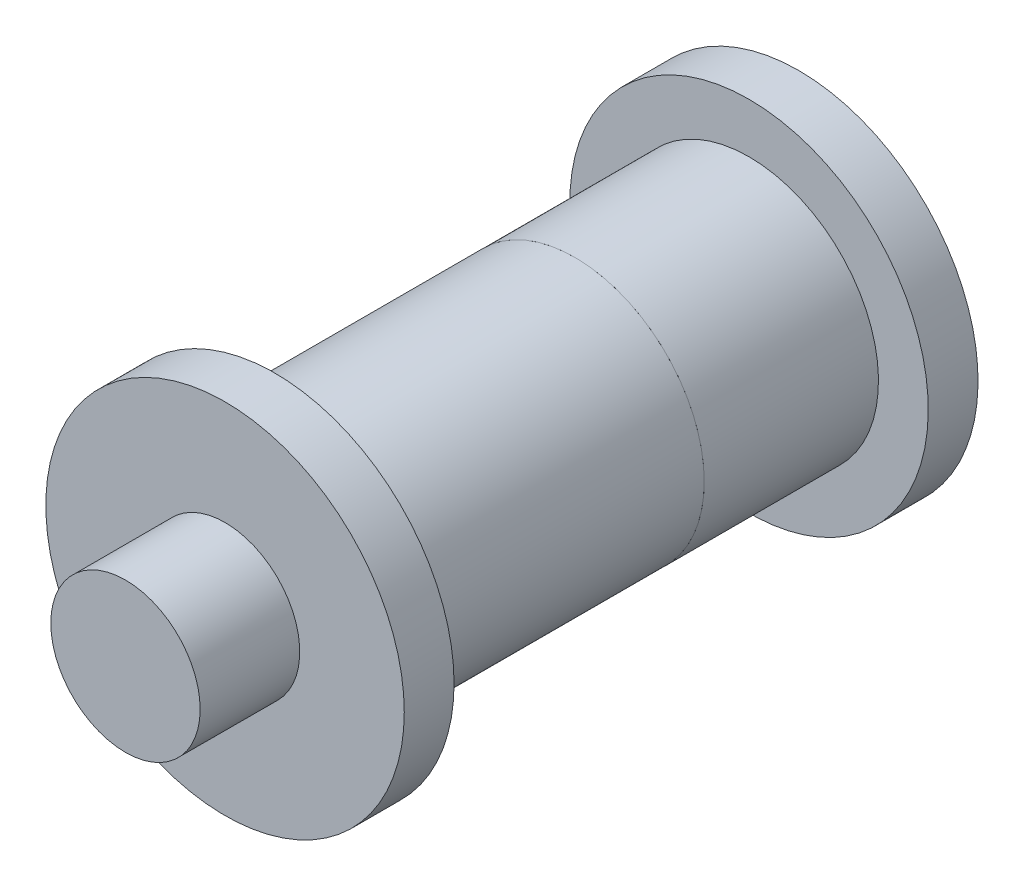
SolidWorks part; units mm, degrees
material "ABS"
ref_plane "Front Plane" through (0, 0, 0) normal (0, 0, 1) x (1, 0, 0)
ref_plane "Top Plane" through (0, 0, 0) normal (0, 1, 0) x (1, 0, 0)
ref_plane "Right Plane" through (0, 0, 0) normal (1, 0, 0) x (0, 0, -1)
sketch "Sketch2" plane through (0, 0, 0) normal (1, 0, 0) x (0, 0, -1)
  line L0 (0, 0) -> (0, 5.2)
  line L1 (0, 5.2) -> (7, 5.2)
  line L2 (7, 5.2) -> (7, 7.2)
  line L3 (7, 7.2) -> (9, 7.2)
  line L5 (11, 0) -> (0, 0)
  line L6 (9, 7.2) -> (9, 2.5)
  line L7 (9, 2.5) -> (11, 2.5)
  line L8 (11, 2.5) -> (11, 0)
  point P2 (5.9162, 5.2)
  point P7 (0, 0)
  point P11 (11.008, 0)
  point P12 (0, 0)
  point P13 (13.0983, 0)
  point P14 (15.3628, 0)
  dimension "D3" = 5.2
  dimension "D4" = 2
  dimension "D1" = 2
  dimension "D2" = 2.5
  dimension "D5" = 11
  dimension "D6" = 2
revolve "Revolve1" add sketch "Sketch2" angle 360 about L5
sketch "Sketch4" plane through (0, 0, -11) normal (0, 0, -1) x (-1, 0, 0)
  circle A0 centre (0, 0) radius 1.6
  dimension "D1" = 3.2
extrude "Cut-Extrude2" cut sketch "Sketch4" against normal blind 0.5
sketch "Sketch5" plane through (0, 0, 0) normal (1, 0, 0) x (0, 0, -1)
  line L0 (0, 0) -> (0, 5.2)
  line L1 (0, 5.2) -> (-12.05, 5.2)
  line L2 (-12.05, 5.2) -> (-12.05, 7.2)
  line L3 (-12.05, 7.2) -> (-14.05, 7.2)
  line L4 (-14.05, 7.2) -> (-14.05, 0)
  line L7 (-14.05, 0) -> (0, 0)
  line L8 (7, 7.2) -> (7, -7.2) construction
  line L9 (9, 7.2) -> (7, 7.2) construction
  point P9 (-14.05, 0)
  point P14 (-14.05, 0.0855)
  dimension "D1" = 19.05
  dimension "D2" = 2
revolve "Revolve2" add sketch "Sketch5" angle 360 about L7
sketch "Sketch3" plane through (0, 0, 0) normal (0, 0, 1) x (1, 0, 0)
  line L0 (-1.1619, 1.1) -> (1.1619, 1.1)
  arc A0 (-1.1619, 1.1) -> (1.1619, 1.1) centre (0, 0) ccw
  arc A1 (1.1619, 1.1) -> (-1.1619, 1.1) centre (0, 0) ccw construction
  point P3 (0, -1.6)
  dimension "D1" = 3.2
  dimension "D2" = 2.7
extrude "Cut-Extrude1" cut sketch "Sketch3" against normal through all both and the other way through all
sketch "Sketch6" plane through (0, 0, 14.05) normal (0, 0, 1) x (1, 0, 0)
  circle A0 centre (0, 0) radius 3
  dimension "D1" = 6
extrude "Boss-Extrude2" add sketch "Sketch6" along normal blind 4
equation "\"D3@Sketch2\"=10.4/2"
equation "\"D1@Sketch5\"=0.75in"
